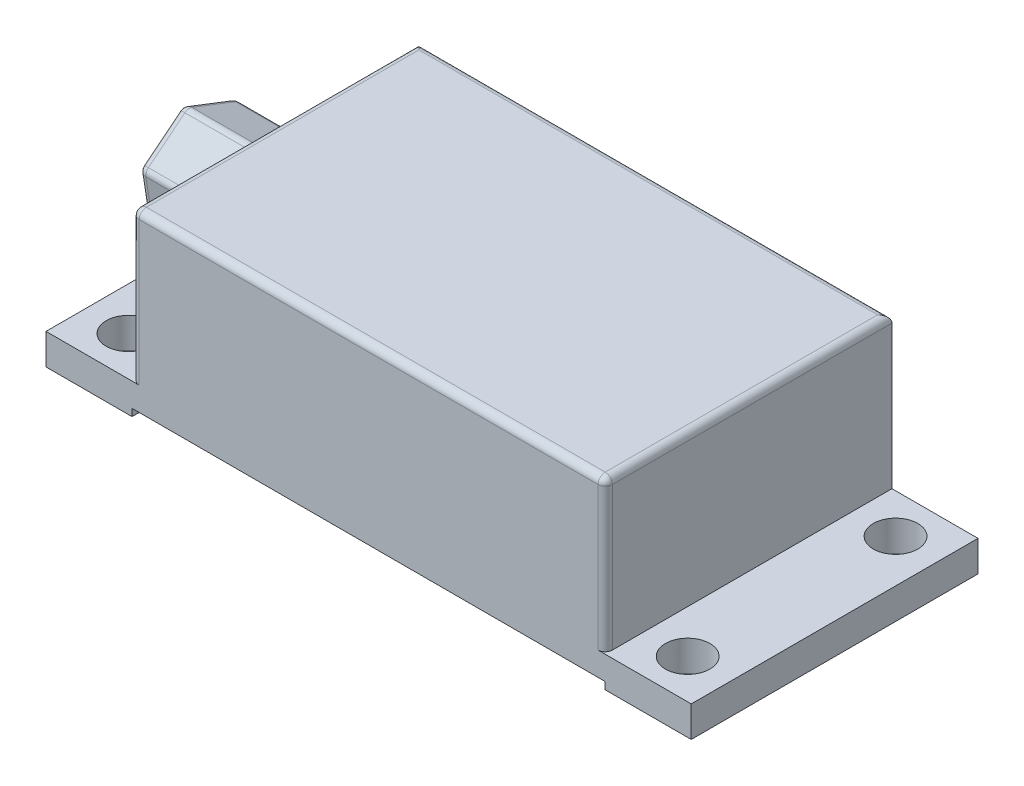
SolidWorks part; units mm, degrees
ref_plane "前视基准面" through (0, 0, 0) normal (0, 0, 1) x (1, 0, 0)
ref_plane "上视基准面" through (0, 0, 0) normal (0, 1, 0) x (1, 0, 0)
ref_plane "右视基准面" through (0, 0, 0) normal (1, 0, 0) x (0, 0, -1)
sketch "草图13" plane through (0, 0, 0) normal (0, 1, 0) x (1, 0, 0)
  line L0 (45, 0) -> (-45, 0)
  line L1 (-45, 0) -> (-45, 40)
  line L2 (-45, 40) -> (45, 40)
  line L3 (45, 40) -> (45, 0)
  point P4 (0, 0)
  point P10 (0, 0)
  dimension "D1" = 40
  dimension "D2" = 90
extrude "凸台-拉伸8" add sketch "草图13" along normal blind 25.3
sketch "草图15" plane through (0, 0, 0) normal (0, -1, 0) x (1, 0, 0)
  line L0 (33, 0) -> (-33, 0)
  line L1 (-45, 0) -> (45, 0) construction
  line L2 (-33, 0) -> (-33, -40)
  line L3 (45, -40) -> (-45, -40) construction
  line L4 (-33, -40) -> (33, -40)
  line L5 (33, -40) -> (33, 0)
  point P0 (26.1545, -40)
  point P5 (0, 0)
  dimension "D1" = 66
extrude "切除-拉伸3" cut sketch "草图15" against normal blind 1
sketch "草图17" plane through (0, 0, 0) normal (0, 0, 1) x (1, 0, 0)
  line L0 (-45, 0) -> (-45, 4.3)
  line L1 (-45, 25.3) -> (-45, 0) construction
  line L2 (-45, 4.3) -> (-33, 4.3)
  line L3 (-33, 4.3) -> (-33, 25.3)
  line L4 (-45, 25.3) -> (45, 25.3) construction
  line L5 (0, 1) -> (0, 25.3)
  line L6 (33, 1) -> (-33, 1) construction
  line L7 (45, 0) -> (45, 4.3)
  line L8 (45, 4.3) -> (33, 4.3)
  line L9 (33, 4.3) -> (33, 25.3)
  line L10 (-45, 4.3) -> (-45, 25.3)
  line L11 (-45, 25.3) -> (-33, 25.3)
  line L12 (33, 25.3) -> (45, 25.3)
  line L13 (45, 25.3) -> (45, 4.3)
  line M10 (45, 0) -> (45, 25.3)
  line M11 (45, 25.3) -> (-45, 25.3)
  line M12 (-45, 25.3) -> (-45, 0)
extrude "切除-拉伸4" cut sketch "草图17" against normal blind 40 contours L2 L3 M11 M12 | L9 L8 M10 M11
sketch "草图19" plane through (-33, 0, 0) normal (-1, 0, 0) x (0, 0, 1)
  line L0 (-40, 25.3) -> (0, 4.3)
  line L7 (-40, 25.3) -> (0, 25.3) construction
  line L8 (-40, 4.3) -> (-40, 25.3) construction
  line L9 (-40, 4.3) -> (0, 4.3) construction
  line L10 (0, 25.3) -> (-40, 4.3)
  line L12 (-12.839, 17.5719) -> (-18.8201, 22.3876)
  line L13 (-18.8201, 22.3876) -> (-25.981, 19.6156)
  line L14 (-25.981, 19.6156) -> (-27.161, 12.0281)
  line L15 (-27.161, 12.0281) -> (-21.1799, 7.2124)
  line L16 (-21.1799, 7.2124) -> (-14.019, 9.9844)
  line L17 (-14.019, 9.9844) -> (-12.839, 17.5719)
  circle A0 centre (-20, 14.8) radius 6.65 construction
  point P11 (0, 0)
  dimension "D1" = 6.65
extrude "凸台-拉伸10" add sketch "草图19" along normal up to surface (12 mm away) contours L0 L17 L12 L10 | L13 L14 L0 L10 L12 | L14 L15 L10 L0 | L16 L17 L0 L10 L15 up to face at (-45, 2.15, -20)
fillet "圆角1" radius 1 1 edges at (0, 25.3, 0)
fillet "圆角2" radius 1 7 edges at (33, 14.3, 0) (33, 25.0071, -0.2929) (-33, 14.3, 0) (-33, 25.0071, -0.2929) (33, 25.3, -20.5) (0, 25.3, -40) (-33, 25.3, -20.5)
fillet "圆角3" radius 1 12 edges at (-39, 12.0281, -27.161) (-39, 9.9844, -14.019) (-39, 7.2124, -21.1799) (-45, 15.8219, -26.571) (-45, 9.6203, -24.1705) (-45, 8.5984, -17.5994) (-45, 13.7781, -13.429) (-39, 17.5719, -12.839) (-45, 19.9797, -15.8295) (-39, 19.6156, -25.981) (-45, 21.0016, -22.4006) (-39, 22.3876, -18.8201)
sketch "草图22" plane through (0, 4.3, 0) normal (0, 1, 0) x (1, 0, 0)
  line L0 (-45, 37.6) -> (-33, 37.6)
  line L1 (-45, 40) -> (-45, 0) construction
  line L2 (-33, 1) -> (-33, 40) construction
  line L3 (-45, 40) -> (-33, 40) construction
  line L4 (-42.1, 40) -> (-42.1, 27.0841)
  line L5 (-33, 27.0841) -> (-44, 27.0841) construction
  line L6 (-45, 20) -> (45, 20) construction
  line L7 (45, 40) -> (45, 0) construction
  line L8 (0, 40.9613) -> (0, -0.7136)
  circle A0 centre (-39, 34.5) radius 3.1
  circle A1 centre (39, 34.5) radius 3.1
  circle A2 centre (39, 5.5) radius 3.1
  circle A3 centre (-39, 5.5) radius 3.1
  point P27 (0, 0)
  dimension "D1" = 6.2
  dimension "D2" = 2.4
  dimension "D3" = 2.9
extrude "切除-拉伸5" cut sketch "草图22" against normal up to next contours A3 | A2 | A1 | A0
